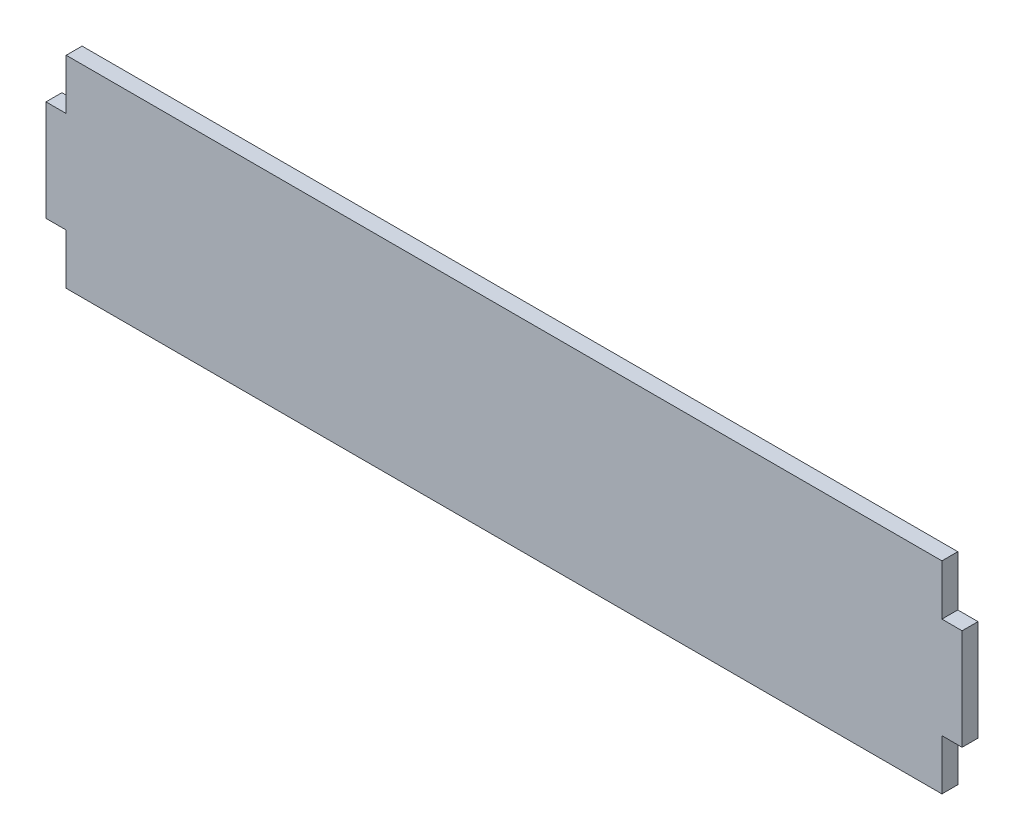
SolidWorks part; units mm, degrees
ref_plane "Front Plane" through (0, 0, 0) normal (0, 0, 1) x (1, 0, 0)
ref_plane "Top Plane" through (0, 0, 0) normal (0, 1, 0) x (1, 0, 0)
ref_plane "Right Plane" through (0, 0, 0) normal (1, 0, 0) x (0, 0, -1)
sketch "Sketch1" plane through (0, 0, 0) normal (0, 0, 1) x (1, 0, 0)
  line L0 (-75.3383, 22.86) -> (-75.3383, 19.05)
  line L1 (-75.3383, 25.4) -> (34.8456, 25.4)
  line L2 (-77.8783, 19.05) -> (-77.8783, 6.35)
  line L3 (-75.3383, 0) -> (34.8456, 0)
  line L4 (37.3856, 19.05) -> (37.3856, 6.35)
  line L8 (34.8456, 22.86) -> (34.8456, 19.05)
  line L10 (-77.8783, 19.05) -> (-75.3383, 19.05)
  line L11 (-77.8783, 6.35) -> (-75.3383, 6.35)
  line L12 (34.8456, 22.86) -> (34.8456, 25.4)
  line L13 (34.8456, 2.54) -> (34.8456, 0)
  line L14 (-75.3383, 22.86) -> (-75.3383, 25.4)
  line L15 (-75.3383, 2.54) -> (-75.3383, 0)
  line L16 (-77.8783, 25.4) -> (-77.8783, 0) construction
  line L17 (-77.8783, 25.4) -> (37.3856, 25.4) construction
  line L18 (-77.8783, 0) -> (37.3856, 0) construction
  line L19 (37.3856, 25.4) -> (37.3856, 0) construction
  line L20 (34.8456, 19.05) -> (37.3856, 19.05)
  line L21 (-75.3383, 6.35) -> (-75.3383, 2.54)
  line L22 (-75.3383, 22.86) -> (-75.3383, 2.54) construction
  line L23 (34.8456, 6.35) -> (37.3856, 6.35)
  line L26 (-75.3383, 2.54) -> (34.8456, 2.54) construction
  line L29 (-75.3383, 22.86) -> (34.8456, 22.86) construction
  line L30 (34.8456, 6.35) -> (34.8456, 2.54)
  line L31 (34.8456, 22.86) -> (34.8456, 2.54) construction
  point P0 (-20.1774, 12.7)
  dimension "D4" = 6.35
  dimension "D5" = 6.35
  dimension "D3" = 2.54
extrude "Boss-Extrude1" add sketch "Sketch1" along normal blind 2
